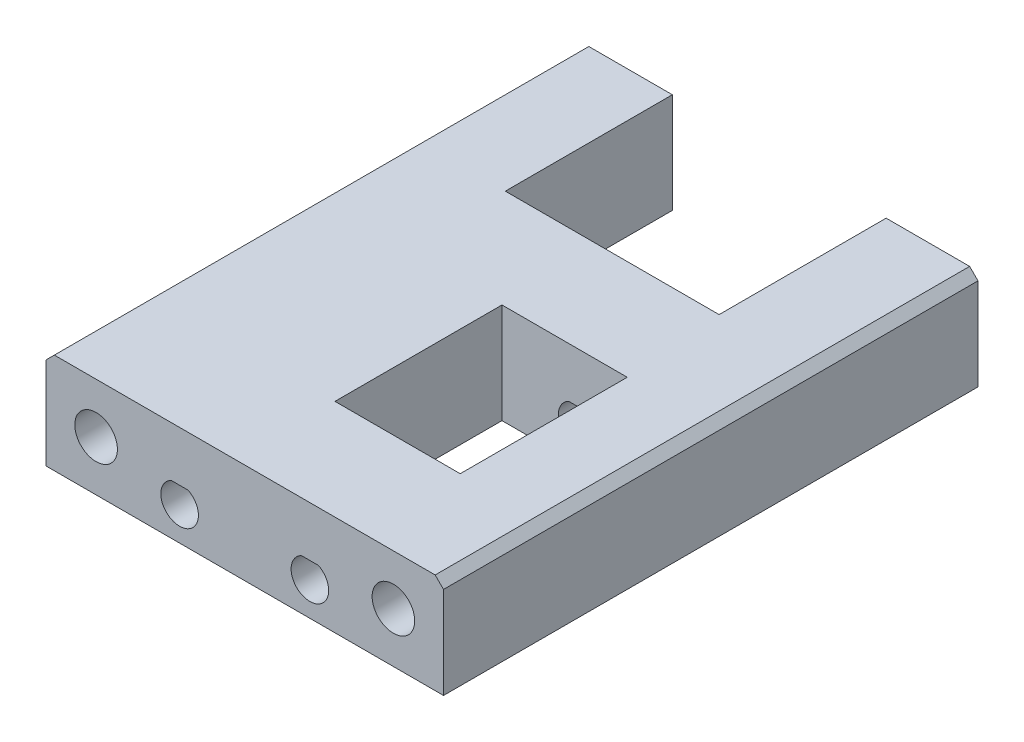
SolidWorks part; units mm, degrees
ref_plane "Front Plane" through (0, 0, 0) normal (0, 0, 1) x (1, 0, 0)
ref_plane "Top Plane" through (0, 0, 0) normal (0, 1, 0) x (1, 0, 0)
ref_plane "Right Plane" through (0, 0, 0) normal (1, 0, 0) x (0, 0, -1)
sketch "Sketch1" plane through (0, 0, 0) normal (0, 0, 1) x (1, 0, 0)
  line L0 (0, 0) -> (47.6, 0)
  line L1 (47.6, 0) -> (47.6, 6)
  line L2 (47.6, 6) -> (44.15, 6)
  line L3 (0, 6) -> (0, 0)
  line L4 (3.45, 6) -> (0, 6)
  line L5 (39.05, 6) -> (8.55, 6)
  arc A0 (3.45, 6) -> (8.55, 6) centre (6, 6) ccw
  arc A1 (39.05, 6) -> (44.15, 6) centre (41.6, 6) ccw
  dimension "D3" = 5.1
  dimension "D4" = 5.1
  dimension "D5" = 6
  dimension "D6" = 6
  dimension "D1" = 47.6
  dimension "D2" = 6
extrude "Boss-Extrude1" add sketch "Sketch1" along normal blind 44
sketch "Sketch2" plane through (0, 0, 44) normal (0, 0, 1) x (1, 0, 0)
  line L0 (0, 4) -> (47.6, 4) construction
  line L3 (0, 0) -> (47.6, 0) construction
  line L4 (0, 6) -> (0, 0) construction
  line L5 (47.6, 0) -> (47.6, 6) construction
  circle A0 centre (16, 4) radius 2.25
  circle A1 centre (31.6, 4) radius 2.25
  arc A2 (3.45, 6) -> (8.55, 6) centre (6, 6) ccw construction
  arc A3 (39.05, 6) -> (44.15, 6) centre (41.6, 6) ccw construction
  dimension "D1" = 4.5
  dimension "D2" = 4.5
  dimension "D3" = 10
  dimension "D4" = 10
  dimension "D5" = 4
extrude "Cut-Extrude1" cut sketch "Sketch2" against normal through all
sketch "Sketch4" plane through (0, 0, 0) normal (0, 0, -1) x (-1, 0, 0)
  line L0 (-11, 6) -> (-11, 0)
  line L1 (-39.05, 6) -> (-32.6308, 6) construction
  line L2 (0, 0) -> (-47.6, 0) construction
  line L3 (-11, 0) -> (0, 0)
  line L4 (0, 0) -> (0, 6)
  line L5 (0, 6) -> (-3.45, 6)
  line L6 (-11, 6) -> (-8.55, 6)
  line L7 (-36.6, 6) -> (-36.6, 0)
  line L8 (-36.6, 0) -> (-47.6, 0)
  line L9 (-47.6, 0) -> (-47.6, 6)
  line L10 (-47.6, 6) -> (-44.15, 6)
  line L11 (-39.05, 6) -> (-36.6, 6)
  arc A0 (-8.55, 6) -> (-3.45, 6) centre (-6, 6) ccw
  arc A1 (-44.15, 6) -> (-39.05, 6) centre (-41.6, 6) ccw
  arc A2 (-44.15, 6) -> (-39.05, 6) centre (-41.6, 6) ccw construction
  dimension "D1" = 11
  dimension "D2" = 2.55
  dimension "D3" = 11
extrude "Boss-Extrude2" add sketch "Sketch4" along normal blind 20
sketch "Sketch5" plane through (0, 0, 44) normal (0, 0, 1) x (1, 0, 0)
  line L0 (0, 6) -> (0, 12)
  line L1 (0, 12) -> (47.6, 12)
  line L2 (47.6, 12) -> (47.6, 6)
  line L3 (0, 6) -> (3.45, 6)
  line L4 (47.6, 6) -> (44.15, 6)
  line L5 (8.55, 6) -> (39.05, 6)
  arc A0 (8.55, 6) -> (3.45, 6) centre (6, 6) ccw
  arc A1 (44.15, 6) -> (39.05, 6) centre (41.6, 6) ccw
  dimension "D1" = 6
extrude "Boss-Extrude3" add sketch "Sketch5" against normal up to surface (64 mm away) up to face at (5.6667, 3.575, -20)
sketch "Sketch6" plane through (0, 6, 0) normal (0, -1, 0) x (1, 0, 0)
  line L0 (47.6, -20) -> (36.6, -20) construction
  line L1 (11, 0) -> (36.6, 0)
  line L2 (11, 0) -> (11, -20)
  line L3 (11, -20) -> (36.6, -20)
  line L4 (36.6, 0) -> (36.6, -20)
  line L5 (36.6, -20) -> (36.6, 0) construction
extrude "Cut-Extrude2" cut sketch "Sketch6" against normal through all
chamfer "Chamfer1" distance 10 angle 5 2 edges at (39.05, 6, -20) (3.45, 6, -20)
chamfer "Chamfer2" distance 1 angle 45 2 edges at (0, 12, 12) (47.6, 12, 12)
sketch "Sketch7" plane through (0, 0, 0) normal (0, -1, 0) x (1, 0, 0)
  line L0 (11, 0) -> (36.6, 0) construction
  line L1 (37.6, 12) -> (22.6, 12)
  line L2 (37.6, 12) -> (37.6, 32)
  line L3 (37.6, 32) -> (22.6, 32)
  line L4 (22.6, 12) -> (22.6, 32)
  line L5 (47.6, 44) -> (47.6, -20) construction
  dimension "D1" = 12
  dimension "D2" = 10
  dimension "D3" = 20
  dimension "D4" = 15
extrude "Cut-Extrude3" cut sketch "Sketch7" against normal through all
